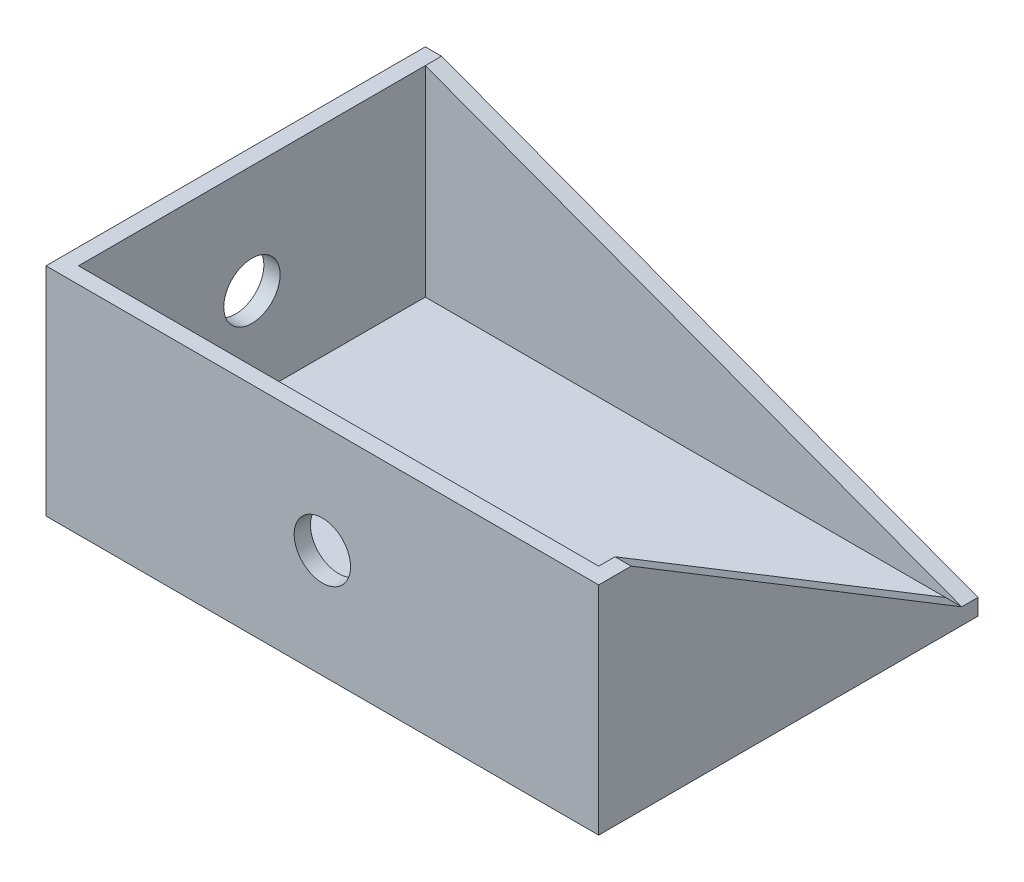
SolidWorks part; units mm, degrees
ref_plane "前视基准面" through (0, 0, 0) normal (0, 0, 1) x (1, 0, 0)
ref_plane "上视基准面" through (0, 0, 0) normal (0, 1, 0) x (1, 0, 0)
ref_plane "右视基准面" through (0, 0, 0) normal (1, 0, 0) x (0, 0, -1)
sketch "草图1" plane through (0, 0, 0) normal (0, 1, 0) x (1, 0, 0)
  line L1 (0, 0) -> (51, 0)
  line L2 (0, 0) -> (0, 35)
  line L3 (0, 35) -> (51, 35)
  line L4 (51, 0) -> (51, 35)
  dimension "D1" = 51
  dimension "D2" = 35
extrude "凸台-拉伸1" add sketch "草图1" along normal blind 20
sketch "草图2" plane through (0, 20, 0) normal (0, 1, 0) x (1, 0, 0)
  line L8 (1.5, 33.5) -> (1.5, 1.5)
  line L9 (1.5, 1.5) -> (49.5, 1.5)
  line L10 (49.5, 1.5) -> (49.5, 33.5)
  line L11 (49.5, 33.5) -> (1.5, 33.5)
  line L12 (1.5, 33.5) -> (1.5, 1.5)
  line L13 (1.5, 1.5) -> (49.5, 1.5)
  line L14 (49.5, 1.5) -> (49.5, 33.5)
  line L15 (49.5, 33.5) -> (1.5, 33.5)
  dimension "D1" = 1.5
extrude "切除-拉伸1" cut sketch "草图2" against normal offset from surface (18.5 mm away) 1.5 up to face at (25.5, 0, -17.5)
sketch "草图3" plane through (0, 0, 0) normal (0, 0, 1) x (1, 0, 0)
  line L0 (0, 10) -> (51, 10) construction
  line L1 (0, 20) -> (0, 0) construction
  line L2 (51, 20) -> (51, 0) construction
  circle A0 centre (25.5, 10) radius 2.6
  dimension "D1" = 5.2
extrude "切除-拉伸2" cut sketch "草图3" against normal blind 3
sketch "草图4" plane through (0, 0, 0) normal (-1, 0, 0) x (0, 0, 1)
  line L0 (-35, 10) -> (0, 10) construction
  line L1 (-35, 20) -> (-35, 0) construction
  line L2 (0, 20) -> (0, 0) construction
  circle A0 centre (-17.5, 10) radius 2.6
  dimension "D1" = 5.2
extrude "切除-拉伸3" cut sketch "草图4" against normal blind 3
sketch "草图5" plane through (0, 0, -35) normal (0, 0, -1) x (-1, 0, 0)
  line L0 (-51, 20) -> (-1.5, 20)
  line L1 (-51, 20) -> (0, 20) construction
  line L2 (-1.5, 20) -> (-51, 1.5)
  line L3 (-51, 20) -> (-51, 0) construction
  line L4 (-51, 1.5) -> (-51, 20)
  line L5 (0, 20) -> (0, 0) construction
  line L6 (-51, 0) -> (0, 0) construction
  dimension "D1" = 1.5
  dimension "D2" = 1.5
extrude "切除-拉伸4" cut sketch "草图5" against normal blind 1.5
sketch "草图6" plane through (51, 0, 0) normal (1, 0, 0) x (0, 0, -1)
  line L0 (33.5, 20) -> (33.5, 1.5)
  line L1 (33.5, 1.5) -> (3, 20)
  line L2 (33.5, 20) -> (1.5, 20) construction
  line L3 (3, 20) -> (33.5, 20)
  line L4 (0, 20) -> (0, 0) construction
  dimension "D1" = 3
extrude "切除-拉伸5" cut sketch "草图6" against normal blind 3
